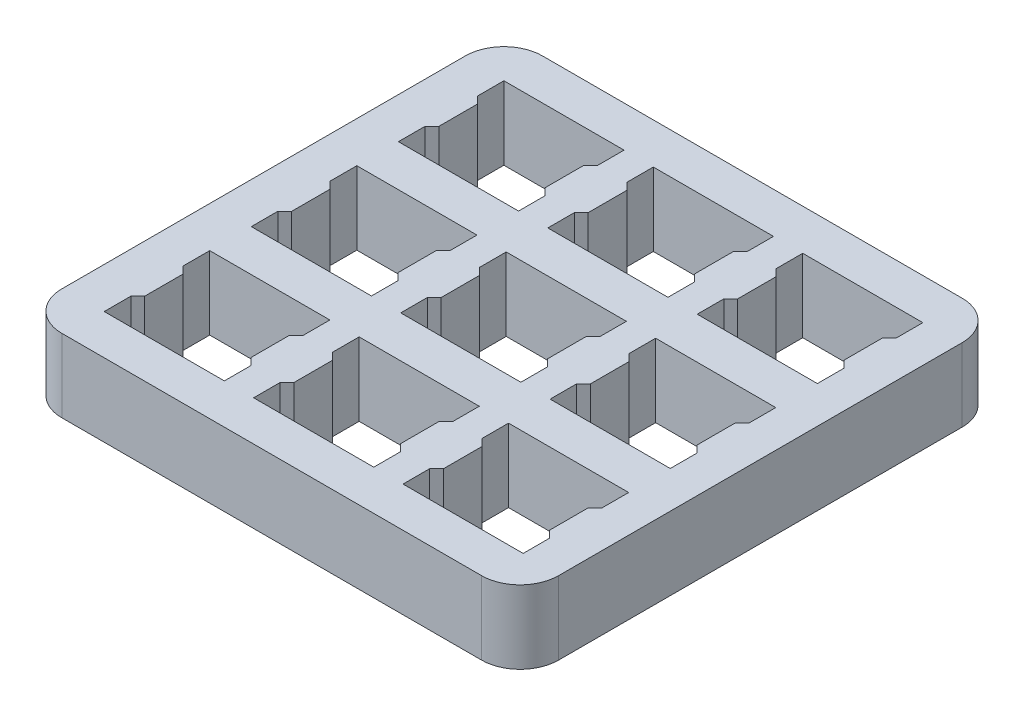
SolidWorks part; units mm, degrees
ref_plane "Plan de face" through (0, 0, 0) normal (0, 0, 1) x (1, 0, 0)
ref_plane "Plan de dessus" through (0, 0, 0) normal (0, 1, 0) x (1, 0, 0)
ref_plane "Plan de droite" through (0, 0, 0) normal (1, 0, 0) x (0, 0, -1)
sketch "Esquisse1" plane through (0, 0, 0) normal (0, 1, 0) x (1, 0, 0)
  line L1 (-32.25, 31.2) -> (32.25, 31.2)
  line L2 (-32.25, 31.2) -> (-32.25, -31.2)
  line L3 (-32.25, -31.2) -> (32.25, -31.2)
  line L4 (32.25, 31.2) -> (32.25, -31.2)
  line L5 (-32.25, 31.2) -> (32.25, -31.2) construction
  line L6 (-32.25, -31.2) -> (32.25, 31.2) construction
  point P0 (0, 0)
  dimension "D1" = 64.5
  dimension "D2" = 62.4
extrude "Boss.-Extru.1" add sketch "Esquisse1" along normal blind 9.5
sketch "Esquisse2" plane through (0, 9.5, 0) normal (0, 1, 0) x (1, 0, 0)
  line L0 (-26.95, 25.9) -> (-11.35, 25.9)
  line L1 (-11.35, 25.9) -> (-11.35, 22.45)
  line L2 (-11.35, 22.45) -> (-12.25, 21.55)
  line L3 (-12.25, 21.55) -> (-12.25, 16.55)
  line L4 (-12.25, 16.55) -> (-11.35, 15.65)
  line L5 (-11.35, 15.65) -> (-11.35, 12.2)
  line L6 (-11.35, 12.2) -> (-26.95, 12.2)
  line L7 (-26.95, 12.2) -> (-26.95, 15.65)
  line L8 (-26.95, 15.65) -> (-26.05, 16.55)
  line L9 (-26.05, 16.55) -> (-26.05, 21.55)
  line L10 (-26.05, 21.55) -> (-26.95, 22.45)
  line L11 (-26.95, 22.45) -> (-26.95, 25.9)
  line L12 (32.25, 31.2) -> (-32.25, 31.2) construction
  line L13 (-32.25, 31.2) -> (-32.25, -31.2) construction
  line L14 (-7.55, 25.9) -> (8.05, 25.9)
  line L15 (8.05, 25.9) -> (8.05, 22.45)
  line L16 (8.05, 22.45) -> (7.15, 21.55)
  line L17 (7.15, 21.55) -> (7.15, 16.55)
  line L18 (7.15, 16.55) -> (8.05, 15.65)
  line L19 (8.05, 15.65) -> (8.05, 12.2)
  line L20 (8.05, 12.2) -> (-7.55, 12.2)
  line L21 (-7.55, 12.2) -> (-7.55, 15.65)
  line L22 (-7.55, 15.65) -> (-6.65, 16.55)
  line L23 (-6.65, 16.55) -> (-6.65, 21.55)
  line L24 (-6.65, 21.55) -> (-7.55, 22.45)
  line L25 (-7.55, 22.45) -> (-7.55, 25.9)
  line L26 (11.85, 25.9) -> (27.45, 25.9)
  line L27 (27.45, 25.9) -> (27.45, 22.45)
  line L28 (27.45, 22.45) -> (26.55, 21.55)
  line L29 (26.55, 21.55) -> (26.55, 16.55)
  line L30 (26.55, 16.55) -> (27.45, 15.65)
  line L31 (27.45, 15.65) -> (27.45, 12.2)
  line L32 (27.45, 12.2) -> (11.85, 12.2)
  line L33 (11.85, 12.2) -> (11.85, 15.65)
  line L34 (11.85, 15.65) -> (12.75, 16.55)
  line L35 (12.75, 16.55) -> (12.75, 21.55)
  line L36 (12.75, 21.55) -> (11.85, 22.45)
  line L37 (11.85, 22.45) -> (11.85, 25.9)
  line L38 (-7.55, 6.8) -> (8.05, 6.8)
  line L39 (8.05, 6.8) -> (8.05, 3.35)
  line L40 (8.05, 3.35) -> (7.15, 2.45)
  line L41 (7.15, 2.45) -> (7.15, -2.55)
  line L42 (7.15, -2.55) -> (8.05, -3.45)
  line L43 (8.05, -3.45) -> (8.05, -6.9)
  line L44 (8.05, -6.9) -> (-7.55, -6.9)
  line L45 (-7.55, -6.9) -> (-7.55, -3.45)
  line L46 (-7.55, -3.45) -> (-6.65, -2.55)
  line L47 (-6.65, -2.55) -> (-6.65, 2.45)
  line L48 (-6.65, 2.45) -> (-7.55, 3.35)
  line L49 (-7.55, 3.35) -> (-7.55, 6.8)
  line L50 (11.85, 6.8) -> (27.45, 6.8)
  line L51 (27.45, 6.8) -> (27.45, 3.35)
  line L52 (27.45, 3.35) -> (26.55, 2.45)
  line L53 (26.55, 2.45) -> (26.55, -2.55)
  line L54 (26.55, -2.55) -> (27.45, -3.45)
  line L55 (27.45, -3.45) -> (27.45, -6.9)
  line L56 (27.45, -6.9) -> (11.85, -6.9)
  line L57 (11.85, -6.9) -> (11.85, -3.45)
  line L58 (11.85, -3.45) -> (12.75, -2.55)
  line L59 (12.75, -2.55) -> (12.75, 2.45)
  line L60 (12.75, 2.45) -> (11.85, 3.35)
  line L61 (11.85, 3.35) -> (11.85, 6.8)
  line L62 (-7.55, -12.3) -> (8.05, -12.3)
  line L63 (8.05, -12.3) -> (8.05, -15.75)
  line L64 (8.05, -15.75) -> (7.15, -16.65)
  line L65 (7.15, -16.65) -> (7.15, -21.65)
  line L66 (7.15, -21.65) -> (8.05, -22.55)
  line L67 (8.05, -22.55) -> (8.05, -26)
  line L68 (8.05, -26) -> (-7.55, -26)
  line L69 (-7.55, -26) -> (-7.55, -22.55)
  line L70 (-7.55, -22.55) -> (-6.65, -21.65)
  line L71 (-6.65, -21.65) -> (-6.65, -16.65)
  line L72 (-6.65, -16.65) -> (-7.55, -15.75)
  line L73 (-7.55, -15.75) -> (-7.55, -12.3)
  line L74 (11.85, -12.3) -> (27.45, -12.3)
  line L75 (27.45, -12.3) -> (27.45, -15.75)
  line L76 (27.45, -15.75) -> (26.55, -16.65)
  line L77 (26.55, -16.65) -> (26.55, -21.65)
  line L78 (26.55, -21.65) -> (27.45, -22.55)
  line L79 (27.45, -22.55) -> (27.45, -26)
  line L80 (27.45, -26) -> (11.85, -26)
  line L81 (11.85, -26) -> (11.85, -22.55)
  line L82 (11.85, -22.55) -> (12.75, -21.65)
  line L83 (12.75, -21.65) -> (12.75, -16.65)
  line L84 (12.75, -16.65) -> (11.85, -15.75)
  line L85 (11.85, -15.75) -> (11.85, -12.3)
  line L86 (-26.95, 6.8) -> (-11.35, 6.8)
  line L87 (-11.35, 6.8) -> (-11.35, 3.35)
  line L88 (-11.35, 3.35) -> (-12.25, 2.45)
  line L89 (-12.25, 2.45) -> (-12.25, -2.55)
  line L90 (-12.25, -2.55) -> (-11.35, -3.45)
  line L91 (-11.35, -3.45) -> (-11.35, -6.9)
  line L92 (-11.35, -6.9) -> (-26.95, -6.9)
  line L93 (-26.95, -6.9) -> (-26.95, -3.45)
  line L94 (-26.95, -3.45) -> (-26.05, -2.55)
  line L95 (-26.05, -2.55) -> (-26.05, 2.45)
  line L96 (-26.05, 2.45) -> (-26.95, 3.35)
  line L97 (-26.95, 3.35) -> (-26.95, 6.8)
  line L98 (-26.95, -12.3) -> (-11.35, -12.3)
  line L99 (-11.35, -12.3) -> (-11.35, -15.75)
  line L100 (-11.35, -15.75) -> (-12.25, -16.65)
  line L101 (-12.25, -16.65) -> (-12.25, -21.65)
  line L102 (-12.25, -21.65) -> (-11.35, -22.55)
  line L103 (-11.35, -22.55) -> (-11.35, -26)
  line L104 (-11.35, -26) -> (-26.95, -26)
  line L105 (-26.95, -26) -> (-26.95, -22.55)
  line L106 (-26.95, -22.55) -> (-26.05, -21.65)
  line L107 (-26.05, -21.65) -> (-26.05, -16.65)
  line L108 (-26.05, -16.65) -> (-26.95, -15.75)
  line L109 (-26.95, -15.75) -> (-26.95, -12.3)
  dimension "D1" = 15.6
  dimension "D2" = 13.8
  dimension "D3" = 13.7
  dimension "D4" = 5
  dimension "D5" = 5.3
  dimension "D6" = 5.3
  dimension "D7" = 135
  dimension "D8" = 3
  dimension "D9" = 3
extrude "Enlèv. mat.-Extru.1" cut sketch "Esquisse2" against normal through all
fillet "Congé1" radius 5 4 edges at (32.25, 4.75, -31.2) (32.25, 4.75, 31.2) (-32.25, 4.75, -31.2) (-32.25, 4.75, 31.2)
